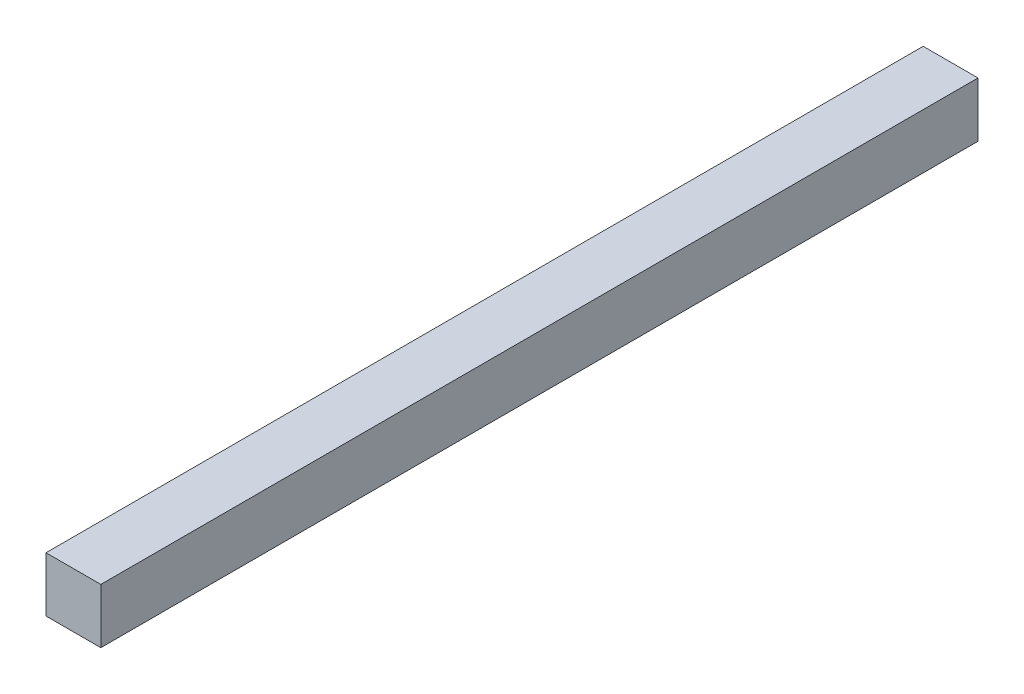
SolidWorks part; units mm, degrees
ref_plane "Front Plane" through (0, 0, 0) normal (0, 0, 1) x (1, 0, 0)
ref_plane "Top Plane" through (0, 0, 0) normal (0, 1, 0) x (1, 0, 0)
ref_plane "Right Plane" through (0, 0, 0) normal (1, 0, 0) x (0, 0, -1)
sketch "Sketch1" plane through (0, 0, 0) normal (0, 0, 1) x (1, 0, 0)
  line L1 (-9.525, -9.525) -> (9.525, -9.525)
  line L2 (-9.525, -9.525) -> (-9.525, 9.525)
  line L3 (-9.525, 9.525) -> (9.525, 9.525)
  line L4 (9.525, -9.525) -> (9.525, 9.525)
  line L5 (-9.525, -9.525) -> (9.525, 9.525) construction
  line L6 (-9.525, 9.525) -> (9.525, -9.525) construction
  point P0 (0, 0)
  dimension "D1" = 19.05
  dimension "D2" = 19.05
extrude "Boss-Extrude1" add sketch "Sketch1" along normal mid plane 304.8 contours L3 L4 L1 L2
